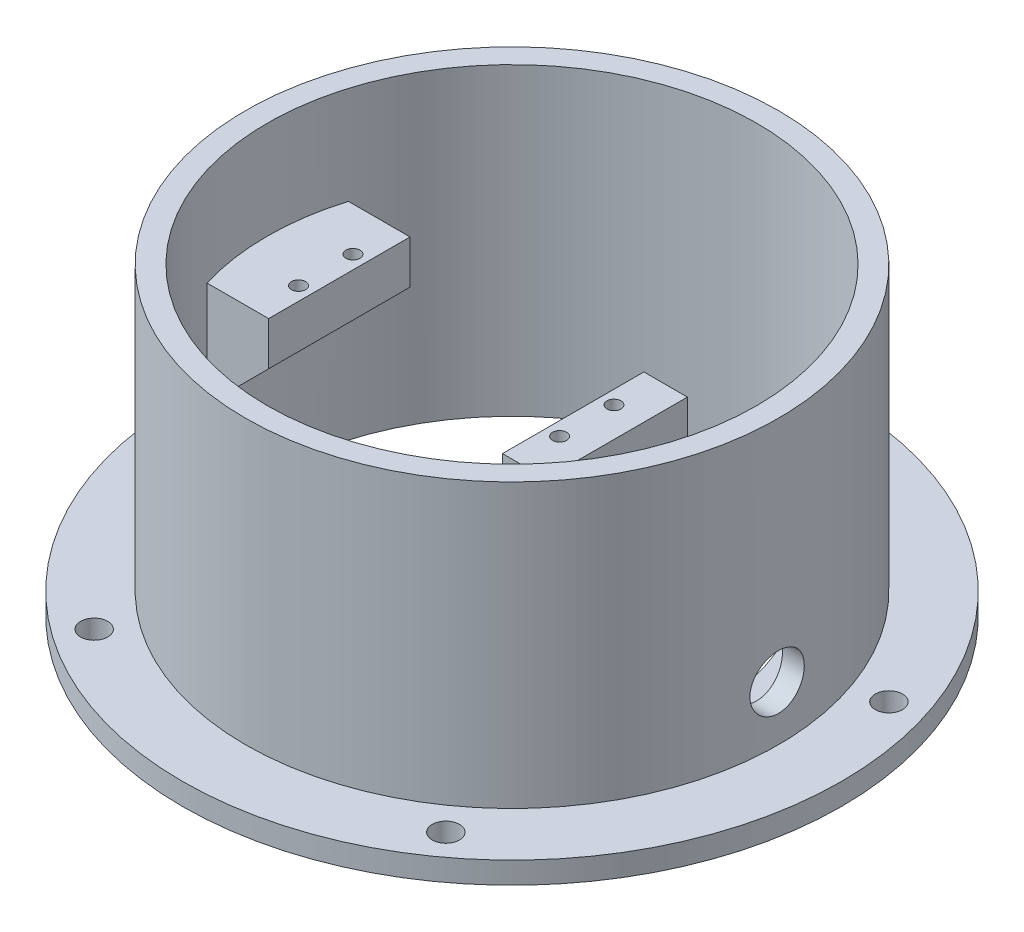
SolidWorks part; units mm, degrees
ref_plane "Front Plane" through (0, 0, 0) normal (0, 0, 1) x (1, 0, 0)
ref_plane "Top Plane" through (0, 0, 0) normal (0, 1, 0) x (1, 0, 0)
ref_plane "Right Plane" through (0, 0, 0) normal (1, 0, 0) x (0, 0, -1)
sketch "Sketch1" plane through (0, 0, 0) normal (0, 1, 0) x (1, 0, 0)
  circle A0 centre (0, 0) radius 60.625
  circle A1 centre (0, 0) radius 45
  dimension "D1" = 121.25
  dimension "D2" = 90
extrude "Boss-Extrude1" add sketch "Sketch1" along normal blind 4 contours A0
sketch "Sketch2" plane through (0, 4, 0) normal (0, 1, 0) x (1, 0, 0)
  circle A0 centre (0, 0) radius 45 construction
  circle A1 centre (0, 0) radius 45
  circle A2 centre (0, 0) radius 49
  dimension "D1" = 4
extrude "Boss-Extrude2" add sketch "Sketch2" along normal blind 52
ref_plane "Plane1" through (0, 36, 0) normal (0, 1, 0) x (1, 0, 0)
sketch "Sketch4" plane through (0, 0, 0) normal (0, 0, 1) x (1, 0, 0)
  line L0 (-60.625, 0) -> (60.625, 0) construction
  line L1 (11.25, 38) -> (19.25, 38)
  line L2 (11.25, 38) -> (11.25, 0)
  line L3 (11.25, 0) -> (19.25, 0)
  line L4 (19.25, 38) -> (19.25, 0)
  line L5 (49, 56) -> (-49, 56) construction
  line L6 (-45, 56) -> (-45, 4)
  line L7 (-31.75, 38) -> (-46.75, 38)
  line L8 (-31.75, 38) -> (-31.75, 30)
  line L9 (-31.75, 30) -> (-46.75, 30)
  line L10 (-46.75, 38) -> (-46.75, 30)
  line L11 (60.625, 4) -> (-60.625, 4) construction
  line L12 (-31.75, 30) -> (-45, 16.75)
  dimension "D1" = 11.25
  dimension "D2" = 8
  dimension "D3" = 18
  dimension "D4" = 43
  dimension "D5" = 15
  dimension "D6" = 8
  dimension "D7" = 45
  dimension "D8" = 18
extrude "Boss-Extrude4" add sketch "Sketch4" along normal mid plane 26 contours L9 L8 L7 L6 | L12 L9 L6 | L1 L4 L3 L2
sketch "Sketch5" plane through (0, 0, 0) normal (0, -1, 0) x (1, 0, 0)
  line L0 (11.25, 13) -> (29.0674, 34.3524)
  line L1 (11.25, -13) -> (29.0674, -34.3524)
  line L2 (11.25, 13) -> (11.25, -13)
  circle A0 centre (0, 0) radius 45 construction
  arc A1 (29.0674, -34.3524) -> (29.0674, 34.3524) centre (0, 0) ccw
extrude "Boss-Extrude5" add sketch "Sketch5" against normal up to surface (4 mm away) contours L0 A1 L1 L2 up to face at (0, 4, 60.625)
sketch "Sketch7" plane through (0, 38, 0) normal (0, 1, 0) x (1, 0, 0)
  line L0 (-31.75, -13) -> (-31.75, 13) construction
  circle A0 centre (-34.25, 5) radius 1.3
  circle A1 centre (-34.25, -5) radius 1.3
  circle A2 centre (13.75, 5) radius 1.3
  circle A3 centre (13.75, -5) radius 1.3
  dimension "D1" = 2.6
  dimension "D2" = 2.6
  dimension "D3" = 10
  dimension "D4" = 5
  dimension "D5" = 2.5
  dimension "D7" = 48
  dimension "D6" = 2
extrude "Cut-Extrude4" cut sketch "Sketch7" against normal blind 7.2
sketch "Sketch9" plane through (11.25, 0, 0) normal (-1, 0, 0) x (0, 0, 1)
  line L0 (13, 0) -> (-13, 0) construction
  line L1 (-5, 29) -> (5, 29)
  line L2 (-5, 29) -> (-5, 0)
  line L3 (-5, 0) -> (5, 0)
  line L4 (5, 29) -> (5, 0)
  line L5 (-5, 29) -> (5, 0) construction
  line L6 (-5, 0) -> (5, 29) construction
  line L7 (0, 0) -> (0, 29) construction
  line L8 (13, 38) -> (-13, 38) construction
  line L10 (5, 5) -> (-5, 5)
  point P0 (0, 14.5)
  dimension "D1" = 10
  dimension "D2" = 9
  dimension "D3" = 5
extrude "Cut-Extrude7" cut sketch "Sketch9" against normal up to surface (8 mm away) contours L10 L4 L1 L2 up to face at (19.25, 21, 0)
ref_plane "Plane2" through (49, 0, 0) normal (1, 0, 0) x (0, 0, -1)
sketch "Sketch11" plane through (49, 0, 0) normal (1, 0, 0) x (0, 0, -1)
  circle A0 centre (0, 14) radius 5
  dimension "D1" = 10
  dimension "D2" = 14
extrude "Cut-Extrude8" cut sketch "Sketch11" against normal up to next
sketch "Sketch12" plane through (0, 4, 0) normal (0, 1, 0) x (1, 0, 0)
  line L5 (27.25, 19.6878) -> (27.25, -19.6878)
  line L6 (27.25, 19.6878) -> (27.25, -19.6878)
  line L9 (24.25, 16.0926) -> (24.25, -16.0926)
  line L10 (19.25, -13) -> (19.25, 13) construction
  line L18 (27.25, -19.6878) -> (29.4795, -22.3597)
  line L19 (29.4795, 22.3597) -> (27.25, 19.6878)
  line L21 (24.25, -16.0926) -> (29.4795, -22.3597)
  line L22 (29.4795, 22.3597) -> (24.25, 16.0926)
  arc A2 (29.4795, -22.3597) -> (29.4795, 22.3597) centre (0, 0) ccw
  arc A3 (29.4795, -22.3597) -> (29.4795, 22.3597) centre (0, 0) ccw
  dimension "D2" = 5
  dimension "D1" = 8
extrude "Cut-Extrude9" cut sketch "Sketch12" against normal through all contours L21 A3 L22 L6 | L6 L22 L9 L21
sketch "Sketch15" plane through (0, 4, 0) normal (0, 1, 0) x (1, 0, 0)
  circle A0 centre (0, 55) radius 2.5
  circle A1 centre (0, 0) radius 60.625 construction
  circle A2 centre (52.3081, 16.9959) radius 2.5
  circle A3 centre (32.3282, -44.4959) radius 2.5
  circle A4 centre (-32.3282, -44.4959) radius 2.5
  circle A5 centre (-52.3081, 16.9959) radius 2.5
  dimension "D1" = 5
  dimension "D2" = 55
  dimension "D3" = 5
extrude "Cut-Extrude10" cut sketch "Sketch15" against normal blind 10
